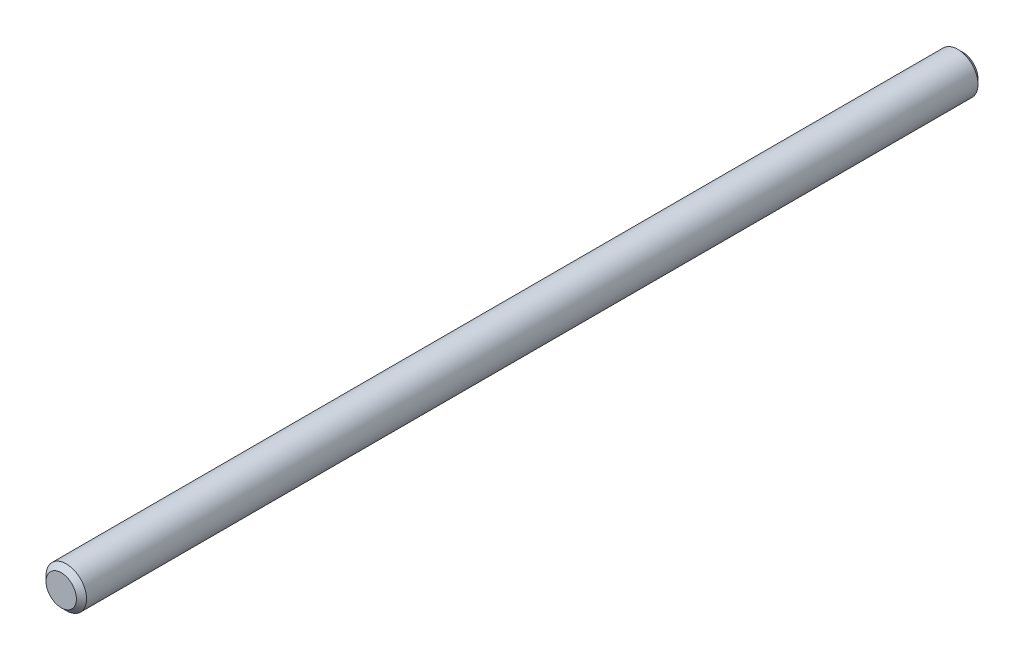
SolidWorks part; units mm, degrees
material "Stainless Steel (ferritic)"
ref_plane "Front Plane" through (0, 0, 0) normal (0, 0, 1) x (1, 0, 0)
ref_plane "Top Plane" through (0, 0, 0) normal (0, 1, 0) x (1, 0, 0)
ref_plane "Right Plane" through (0, 0, 0) normal (1, 0, 0) x (0, 0, -1)
sketch "Sketch1" plane through (0, 0, 0) normal (0, 0, 1) x (1, 0, 0)
  circle A0 centre (0, 0) radius 2
  dimension "D1" = 4
extrude "Boss-Extrude1" add sketch "Sketch1" along normal mid plane 88.9
chamfer "Chamfer1" distance 0.5 angle 45 2 edges at (2, 0, -44.45) (2, 0, 44.45)
